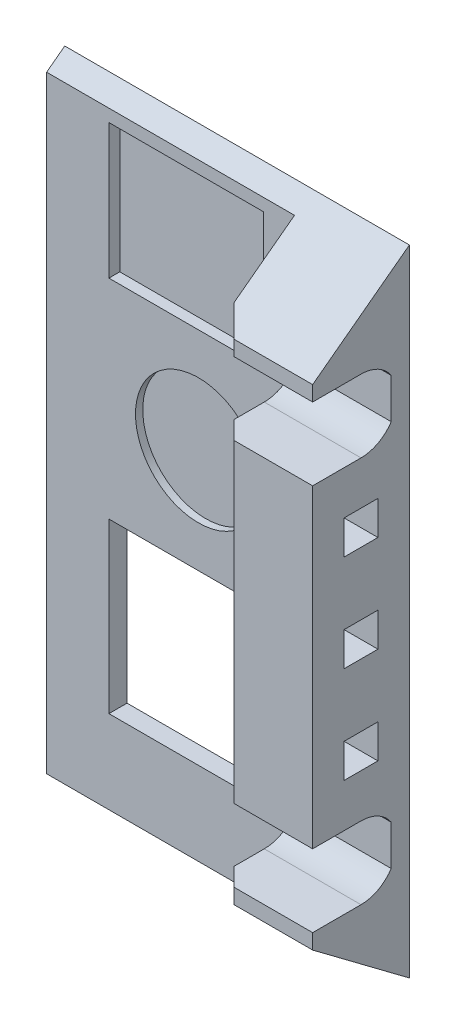
SolidWorks part; units mm, degrees
ref_plane "Plano frontal" through (0, 0, 0) normal (0, 0, 1) x (1, 0, 0)
ref_plane "Plano superior" through (0, 0, 0) normal (0, 1, 0) x (1, 0, 0)
ref_plane "Plano direito" through (0, 0, 0) normal (1, 0, 0) x (0, 0, -1)
sketch "Esboço1" plane through (0, 0, 0) normal (0, 0, 1) x (1, 0, 0)
  line L0 (-5, 0) -> (5, 0) construction
  line L1 (25, 0) -> (-25, 0) construction
  line L2 (0, 0) -> (0, -12.5) construction
  line L3 (25, -12.5) -> (-25, -12.5) construction
  line L4 (-21, 0) -> (-5, 0) construction
  line L5 (-25, -12.5) -> (-25, 12.5)
  line L6 (-25, 12.5) -> (25, 12.5)
  line L7 (0, 12.5) -> (0, 0) construction
  line L8 (20, -12.5) -> (-20, -12.5) construction
  line L12 (-15, -12.5) -> (15, -12.5)
  line L23 (21, 0) -> (5, 0) construction
  line L31 (25, -12.5) -> (25, 12.5)
  line L32 (-25, -12.5) -> (-15, -12.5)
  line L33 (15, -12.5) -> (25, -12.5)
  circle A0 centre (-13, 0) radius 8.3
  circle A1 centre (13, 0) radius 8.3
extrude "Ressalto-extrusão1" add sketch "Esboço1" along normal blind 1.5
sketch "Esboço2" plane through (0, 0, 1.5) normal (0, 0, 1) x (1, 0, 0)
  line L0 (-20, -12.5) -> (-25, -12.5)
  line L1 (0, -12.5) -> (0, 12.5) construction
  line L2 (20, -12.5) -> (-20, -12.5) construction
  line L3 (-25, -12.5) -> (25, -12.5) construction
  line L4 (22, -2.5) -> (22, -9.5)
  line L5 (-25, 12.5) -> (-25, -12.5) construction
  line L6 (-22, -9.5) -> (-15, -9.5)
  line L7 (-15, -9.5) -> (-15, -12.5)
  line L8 (-15, -12.5) -> (-20, -12.5)
  line L9 (-25, -12.5) -> (-25, -2.5)
  line L10 (-25, -2.5) -> (-22, -2.5)
  line L11 (-22, -2.5) -> (-22, -9.5)
  line L12 (25, -2.5) -> (22, -2.5)
  line L13 (25, -12.5) -> (25, -2.5)
  line L14 (15, -12.5) -> (20, -12.5)
  line L15 (25, 12.5) -> (-25, 12.5) construction
  line L16 (15, -9.5) -> (15, -12.5)
  line L17 (-25, 0) -> (25, 0) construction
  line L18 (25, -12.5) -> (25, 12.5) construction
  line L19 (22, -9.5) -> (15, -9.5)
  line L20 (20, -12.5) -> (25, -12.5)
  line L21 (20, 12.5) -> (-20, 12.5) construction
  line L22 (20, 12.5) -> (25, 12.5)
  line L23 (22, 9.5) -> (15, 9.5)
  line L24 (15, 9.5) -> (15, 12.5)
  line L25 (15, 12.5) -> (20, 12.5)
  line L26 (25, 12.5) -> (25, 2.5)
  line L27 (25, 2.5) -> (22, 2.5)
  line L28 (-22, 2.5) -> (-22, 9.5)
  line L29 (-25, 2.5) -> (-22, 2.5)
  line L30 (-25, 12.5) -> (-25, 2.5)
  line L31 (-15, 12.5) -> (-20, 12.5)
  line L32 (-15, 9.5) -> (-15, 12.5)
  line L33 (-22, 9.5) -> (-15, 9.5)
  line L34 (22, 2.5) -> (22, 9.5)
  line L35 (-20, 12.5) -> (-25, 12.5)
extrude "Ressalto-extrusão2" add sketch "Esboço2" along normal blind 6
sketch "Esboço3" plane through (0, -12.5, 0) normal (0, -1, 0) x (1, 0, 0)
  line L0 (-25, 3.75) -> (-15, 3.75) construction
  line L1 (-25, 7.5) -> (-25, 0) construction
  line L2 (-15, 7.5) -> (-15, 1.5) construction
  line L3 (-15, 3.75) -> (-20, 3.75) construction
  line L4 (-20, 3.75) -> (-20, 7.5) construction
  line L5 (-25, 7.5) -> (-15, 7.5) construction
  line L6 (0, 0) -> (0, 8.9122) construction
  line L7 (-21.4, 2.35) -> (-18.6, 2.35)
  line L8 (-21.4, 2.35) -> (-21.4, 5.15)
  line L9 (-21.4, 5.15) -> (-18.6, 5.15)
  line L10 (-18.6, 2.35) -> (-18.6, 5.15)
  line L11 (-21.4, 2.35) -> (-18.6, 5.15) construction
  line L12 (-21.4, 5.15) -> (-18.6, 2.35) construction
  line L13 (-25, 0) -> (25, 0) construction
  line L14 (21.4, 5.15) -> (18.6, 2.35) construction
  line L15 (21.4, 2.35) -> (18.6, 5.15) construction
  line L16 (18.6, 2.35) -> (18.6, 5.15)
  line L17 (21.4, 5.15) -> (18.6, 5.15)
  line L18 (21.4, 2.35) -> (21.4, 5.15)
  line L19 (21.4, 2.35) -> (18.6, 2.35)
extrude "Corte-extrusão1" cut sketch "Esboço3" against normal through all
sketch "Esboço4" plane through (-25, 0, 0) normal (-1, 0, 0) x (0, 0, 1)
  line L2 (3.75, 2.5) -> (3.75, 12.5) construction
  line L5 (3.75, -2.5) -> (3.75, -12.5) construction
  line L9 (0, 12.5) -> (7.5, 12.5) construction
  line L10 (5.15, 8.9) -> (2.35, 8.9)
  line L11 (5.15, 8.9) -> (5.15, 6.1)
  line L12 (5.15, 6.1) -> (2.35, 6.1)
  line L13 (2.35, 8.9) -> (2.35, 6.1)
  line L14 (5.15, 8.9) -> (2.35, 6.1) construction
  line L15 (5.15, 6.1) -> (2.35, 8.9) construction
  line L16 (5.15, -6.1) -> (2.35, -6.1)
  line L17 (5.15, -6.1) -> (5.15, -8.9)
  line L18 (5.15, -8.9) -> (2.35, -8.9)
  line L19 (2.35, -6.1) -> (2.35, -8.9)
  line L20 (5.15, -6.1) -> (2.35, -8.9) construction
  line L21 (5.15, -8.9) -> (2.35, -6.1) construction
  point P12 (3.75, 7.5)
  point P17 (3.75, -7.5)
  point P26 (3.75, 12.5)
extrude "Corte-extrusão2" cut sketch "Esboço4" against normal through all
sketch "Esboço6" plane through (0, 0, 0) normal (0, 0, -1) x (-1, 0, 0)
  line L0 (-25, 12.5) -> (-25, -12.5)
  line L1 (-30, -12.5) -> (-25, -12.5)
  line L2 (-30, -12.5) -> (-30, 12.5)
  line L3 (-30, 12.5) -> (-25, 12.5)
  line L4 (30, -12.5) -> (30, 12.5)
  line L5 (-30, -12.5) -> (30, 12.5) construction
  line L6 (-30, 12.5) -> (30, -12.5) construction
  line L7 (25, 12.5) -> (25, -12.5)
  line L8 (25, 12.5) -> (30, 12.5)
  line L9 (25, -12.5) -> (30, -12.5)
  point P0 (0, 0)
extrude "Ressalto-extrusão5" add sketch "Esboço6" against normal up to surface (7.5 mm away) up to face at (20.6667, -8.1667, 7.5)
sketch "Esboço7" plane through (30, 0, 0) normal (1, 0, 0) x (0, 0, -1)
  line L0 (-2.35, -6.1) -> (-5.15, -6.1) construction
  line L1 (-2.35, -8.9) -> (-2.35, -6.1) construction
  line L2 (-5.15, -8.9) -> (-2.35, -8.9) construction
  line L3 (-5.15, -6.1) -> (-5.15, -8.9) construction
  line L4 (-2.35, -6.1) -> (-5.15, -6.1)
  line L5 (-2.35, -8.9) -> (-2.35, -6.1)
  line L6 (-5.15, -8.9) -> (-2.35, -8.9)
  line L7 (-5.15, -6.1) -> (-5.15, -8.9)
  line L8 (-2.35, 6.1) -> (-2.35, 8.9) construction
  line L9 (-2.35, 8.9) -> (-5.15, 8.9) construction
  line L10 (-5.15, 8.9) -> (-5.15, 6.1) construction
  line L11 (-5.15, 6.1) -> (-2.35, 6.1) construction
  line L12 (-2.35, 6.1) -> (-2.35, 8.9)
  line L13 (-2.35, 8.9) -> (-5.15, 8.9)
  line L14 (-5.15, 8.9) -> (-5.15, 6.1)
  line L15 (-5.15, 6.1) -> (-2.35, 6.1)
extrude "Corte-extrusão3" cut sketch "Esboço7" against normal up to surface (60 mm away) up to face at (-30, 0, 3.75)
sketch "Esboço5" plane through (0, 0, 1.5) normal (0, 0, 1) x (1, 0, 0)
  line L0 (-9, -7.2726) -> (-9, -8.3958)
  line L1 (-17, -7.2726) -> (-17, -8.3958)
  line L2 (-17, 8.3958) -> (-17, 7.2726)
  line L3 (9, -7.2726) -> (9, -8.3958)
  line L4 (-9, 8.3958) -> (-9, 7.2726)
  line L8 (17, 8.3958) -> (17, 7.2726)
  line L10 (9, 8.3958) -> (9, 7.2726)
  line L13 (17, -7.2726) -> (17, -8.3958)
  circle A0 centre (-13, 0) radius 8.3 construction
  circle A1 centre (13, 0) radius 8.3 construction
  arc A2 (-17, 7.2726) -> (-17, -7.2726) centre (-13, 0) ccw
  arc A3 (17, -7.2726) -> (17, 7.2726) centre (13, 0) ccw
  arc A4 (-17, 8.3958) -> (-17, -8.3958) centre (-13, 0) ccw
  arc A5 (17, -8.3958) -> (17, 8.3958) centre (13, 0) ccw
  circle A6 centre (-13, 0) radius 8.3 construction
  circle A7 centre (-13, 0) radius 9.3 construction
  circle A8 centre (13, 0) radius 8.3 construction
  circle A9 centre (13, 0) radius 9.3 construction
  arc A12 (-9, -8.3958) -> (-9, 8.3958) centre (-13, 0) ccw
  arc A13 (-9, -7.2726) -> (-9, 7.2726) centre (-13, 0) ccw
  arc A14 (9, 7.2726) -> (9, -7.2726) centre (13, 0) ccw
  arc A15 (9, 8.3958) -> (9, -8.3958) centre (13, 0) ccw
  dimension "D1" = 1
  dimension "D2" = 1
extrude "Ressalto-extrusão3" add sketch "Esboço5" along normal blind 10
sketch "Esboço8" plane through (0, 0, 0) normal (0, 0, -1) x (-1, 0, 0)
  line L1 (30, 26.25) -> (-30, 26.25)
  line L2 (30, 26.25) -> (30, -26.25)
  line L3 (30, -26.25) -> (-30, -26.25)
  line L4 (-30, 26.25) -> (-30, -26.25)
  line L5 (30, 26.25) -> (-30, -26.25) construction
  line L6 (30, -26.25) -> (-30, 26.25) construction
  circle A0 centre (13, 0) radius 8.3
  circle A1 centre (-13, 0) radius 8.3
  point P6 (0, 0)
extrude "Ressalto-extrusão6" add sketch "Esboço8" against normal blind 1.5
sketch "Esboço9" plane through (0, 0, 1.5) normal (0, 0, 1) x (1, 0, 0)
  line L12 (-15, -12.5) -> (-15, -9.5)
  line L13 (-15, -9.5) -> (-22, -9.5)
  line L14 (-22, -9.5) -> (-22, -2.5)
  line L15 (-22, -2.5) -> (-25, -2.5)
  line L16 (-25, -2.5) -> (-25, 2.5)
  line L17 (-25, 2.5) -> (-22, 2.5)
  line L18 (-22, 2.5) -> (-22, 9.5)
  line L19 (-22, 9.5) -> (-15, 9.5)
  line L20 (-15, 9.5) -> (-15, 12.5)
  line L21 (-15, 12.5) -> (-30, 12.5)
  line L22 (-30, 12.5) -> (-30, -12.5)
  line L23 (-30, -12.5) -> (-15, -12.5)
  line L24 (-15, -12.5) -> (-15, -9.5)
  line L25 (-15, -9.5) -> (-22, -9.5)
  line L26 (-22, -9.5) -> (-22, -2.5)
  line L27 (-22, -2.5) -> (-25, -2.5)
  line L28 (-25, -2.5) -> (-25, 2.5)
  line L29 (-25, 2.5) -> (-22, 2.5)
  line L30 (-22, 2.5) -> (-22, 9.5)
  line L31 (-22, 9.5) -> (-15, 9.5)
  line L32 (-15, 9.5) -> (-15, 12.5)
  line L33 (-15, 12.5) -> (-30, 12.5)
  line L34 (-30, 12.5) -> (-30, -12.5)
  line L35 (-30, -12.5) -> (-15, -12.5)
  dimension "D1" = 0
extrude "Corte-extrusão4" cut sketch "Esboço9" along normal through all
sketch "Esboço10" plane through (0, 0, 1.5) normal (0, 0, 1) x (1, 0, 0)
  line L0 (-24.3, -26.25) -> (-24.3, 26.25)
  line L2 (-24.3, 26.25) -> (-22.3, 26.25)
  line L4 (-22.3, 12) -> (-17.3, 12)
  line L5 (-17.3, 12) -> (-17.3, -12)
  line L6 (-17.3, 0) -> (-24.3, 0) construction
  line L7 (-22.3, 20) -> (-22.3, 12)
  line L8 (-22.3, -20) -> (-22.3, -12)
  line L9 (-22.3, -12) -> (-17.3, -12)
  line L10 (-24.3, -26.25) -> (-22.3, -26.25)
  line L11 (-22.3, 12) -> (-22.3, 16) construction
  line L12 (-22.3, 16) -> (-22.3, 20) construction
  line L13 (-22.3, 20) -> (-17.3, 20)
  line L14 (-17.3, 20) -> (-17.3, 26.25)
  line L15 (-17.3, 26.25) -> (-22.3, 26.25)
  line L16 (-17.3, -26.25) -> (-22.3, -26.25)
  line L17 (-17.3, -20) -> (-17.3, -26.25)
  line L18 (-22.3, -20) -> (-17.3, -20)
  line L19 (-24.3, 0) -> (-22.3, 0) construction
  arc A0 (-17, 8.3958) -> (-17, -8.3958) centre (-13, 0) ccw construction
  point P22 (-22.3, 0)
  dimension "D1" = 12
extrude "Ressalto-extrusão7" add sketch "Esboço10" along normal blind 6.5
sketch "Esboço11" plane through (0, -26.25, 0) normal (0, -1, 0) x (1, 0, 0)
  line L0 (-22.3, 8) -> (-17.3, 8)
  line L1 (-17.3, 8) -> (-17.3, 1.5)
  line L2 (-22.3, 8) -> (-17.3, 1.5)
sketch "Esboço12" plane through (-24.3, 0, 0) normal (-1, 0, 0) x (0, 0, 1)
  line L0 (4, 0) -> (4, 16) construction
  line L1 (0, -26.25) -> (0, 26.25) construction
  line L3 (0, 0) -> (8, 0) construction
  circle A0 centre (4, 16) radius 1.65
  circle A1 centre (4, -16) radius 1.65
  dimension "D1" = 4
sketch "Esboço14" plane through (0, 0, 1.5) normal (0, 0, 1) x (1, 0, 0)
  line L4 (-30, -26.25) -> (-24.3, -26.25)
  line L5 (-24.3, -26.25) -> (-24.3, 26.25)
  line L6 (-24.3, 26.25) -> (-30, 26.25)
  line L7 (-30, 26.25) -> (-30, -26.25)
  line L8 (-30, -26.25) -> (-24.3, -26.25)
  line L9 (-24.3, -26.25) -> (-24.3, 26.25)
  line L10 (-24.3, 26.25) -> (-30, 26.25)
  line L11 (-30, 26.25) -> (-30, -26.25)
  dimension "D1" = 0
extrude "Corte-extrusão8" cut sketch "Esboço14" against normal blind 4.5
sketch "Esboço15" plane through (0, 0, 8) normal (0, 0, 1) x (1, 0, 0)
  line L1 (-17.3, -7.0993) -> (-17.3, 7.0993)
  line L2 (-17.3, -7.0993) -> (-17.3, 7.0993)
  arc A1 (-17.3, 7.0993) -> (-17.3, -7.0993) centre (-13, 0) ccw
  arc A2 (-17.3, 7.0993) -> (-17.3, -7.0993) centre (-13, 0) ccw
  dimension "D1" = 0
extrude "Corte-extrusão9" cut sketch "Esboço15" against normal through all
extrude "Corte-extrusão13" cut sketch "Esboço11" against normal up to surface (6.25 mm away) up to face at (-19.8, -20, 4.75)
sketch "Esboço17" plane through (0, 26.25, 0) normal (0, 1, 0) x (1, 0, 0)
  line L0 (-17.3, -1.5) -> (-17.3, -8)
  line L1 (-17.3, -8) -> (-22.3, -8)
  line L2 (-17.3, -8) -> (-24.3, -8) construction
  line L3 (-22.3, -8) -> (-17.3, -1.5)
extrude "Corte-extrusão14" cut sketch "Esboço17" against normal up to surface (6.25 mm away) up to face at (-19.8, 20, 4.75)
extrude "Corte-extrusão15" cut sketch "Esboço12" against normal blind 4.5
sketch "Esboço19" plane through (-24.3, 0, 0) normal (-1, 0, 0) x (0, 0, 1)
  line L0 (0, 26.25) -> (8, 26.25)
  line L1 (8, 26.25) -> (8, 20.25)
  line L2 (8, 26.25) -> (8, -26.25) construction
  line L3 (8, 20.25) -> (0, 26.25)
  line L4 (0, 0) -> (8, 0) construction
  line L5 (8, -20.25) -> (0, -26.25)
  line L6 (8, -26.25) -> (8, -20.25)
  line L7 (0, -26.25) -> (8, -26.25)
extrude "Corte-extrusão17" cut sketch "Esboço19" against normal through all
sketch "Esboço20" plane through (-22.3, 0, 0) normal (1, 0, 0) x (0, 0, -1)
  circle A0 centre (-4, -16) radius 3.5
  circle A1 centre (-4, 16) radius 3.5
extrude "Corte-extrusão18" cut sketch "Esboço20" along normal blind 5
sketch "Esboço21" plane through (-24.3, 0, 0) normal (-1, 0, 0) x (0, 0, 1)
  line L4 (0, 26.25) -> (0, -26.25)
  line L5 (0, -26.25) -> (8, -20.25)
  line L6 (8, -20.25) -> (8, 20.25)
  line L7 (8, 20.25) -> (0, 26.25)
  line L8 (0, 26.25) -> (0, -26.25)
  line L9 (0, -26.25) -> (8, -20.25)
  line L10 (8, -20.25) -> (8, 20.25)
  line L11 (8, 20.25) -> (0, 26.25)
  circle A0 centre (4, -16) radius 1.65 construction
  circle A1 centre (4, -16) radius 1.65
  circle A2 centre (4, 16) radius 1.65 construction
  circle A3 centre (4, 16) radius 1.65
  dimension "D1" = 0
extrude "Ressalto-extrusão8" add sketch "Esboço21" along normal blind 2.95
sketch "Esboço22" plane through (30, 0, 0) normal (1, 0, 0) x (0, 0, -1)
  line L0 (-2.35, -6.1) -> (-5.15, -6.1) construction
  line L1 (-2.35, -8.9) -> (-2.35, -6.1) construction
  line L2 (-5.15, -8.9) -> (-2.35, -8.9) construction
  line L3 (-5.15, -6.1) -> (-5.15, -8.9) construction
  line L4 (-2.35, 8.9) -> (-5.15, 8.9) construction
  line L5 (-5.15, 8.9) -> (-5.15, 6.1) construction
  line L6 (-2.35, 6.1) -> (-2.35, 8.9) construction
  line L7 (-5.15, 6.1) -> (-2.35, 6.1) construction
  line L8 (-1.5, -25.125) -> (0, -26.25)
  line L9 (0, -26.25) -> (0, 26.25)
  line L10 (0, 26.25) -> (-1.5, 25.125)
  line L11 (-1.5, 25.125) -> (-1.5, 12.5)
  line L12 (-1.5, 12.5) -> (-7.5, 12.5)
  line L13 (-7.5, 12.5) -> (-7.5, -12.5)
  line L14 (-7.5, -12.5) -> (-1.5, -12.5)
  line L15 (-1.5, -12.5) -> (-1.5, -25.125)
  line L16 (-1.5, -25.125) -> (0, -26.25)
  line L17 (0, -26.25) -> (0, 26.25)
  line L18 (0, 26.25) -> (-1.5, 25.125)
  line L19 (-1.5, 25.125) -> (-1.5, 12.5)
  line L20 (-1.5, 12.5) -> (-7.5, 12.5)
  line L21 (-7.5, 12.5) -> (-7.5, -12.5)
  line L22 (-7.5, -12.5) -> (-1.5, -12.5)
  line L23 (-1.5, -12.5) -> (-1.5, -25.125)
  line L24 (-2.35, -6.1) -> (-5.15, -6.1)
  line L25 (-2.35, -8.9) -> (-2.35, -6.1)
  line L26 (-5.15, -8.9) -> (-2.35, -8.9)
  line L27 (-5.15, -6.1) -> (-5.15, -8.9)
  line L28 (-2.35, 8.9) -> (-5.15, 8.9)
  line L29 (-5.15, 8.9) -> (-5.15, 6.1)
  line L30 (-2.35, 6.1) -> (-2.35, 8.9)
  line L31 (-5.15, 6.1) -> (-2.35, 6.1)
  dimension "D1" = 0
extrude "Ressalto-extrusão9" add sketch "Esboço22" along normal blind 1.25
sketch "Esboço23" plane through (0, 0, 7.5) normal (0, 0, 1) x (1, 0, 0)
  line L12 (25, -2.5) -> (22, -2.5)
  line L13 (22, -2.5) -> (22, -9.5)
  line L14 (22, -9.5) -> (15, -9.5)
  line L15 (15, -9.5) -> (15, -12.5)
  line L16 (15, -12.5) -> (31.25, -12.5)
  line L17 (31.25, -12.5) -> (31.25, 12.5)
  line L18 (31.25, 12.5) -> (15, 12.5)
  line L19 (15, 12.5) -> (15, 9.5)
  line L20 (15, 9.5) -> (22, 9.5)
  line L21 (22, 9.5) -> (22, 2.5)
  line L22 (22, 2.5) -> (25, 2.5)
  line L23 (25, 2.5) -> (25, -2.5)
  line L24 (25, -2.5) -> (22, -2.5)
  line L25 (22, -2.5) -> (22, -9.5)
  line L26 (22, -9.5) -> (15, -9.5)
  line L27 (15, -9.5) -> (15, -12.5)
  line L28 (15, -12.5) -> (31.25, -12.5)
  line L29 (31.25, -12.5) -> (31.25, 12.5)
  line L30 (31.25, 12.5) -> (15, 12.5)
  line L31 (15, 12.5) -> (15, 9.5)
  line L32 (15, 9.5) -> (22, 9.5)
  line L33 (22, 9.5) -> (22, 2.5)
  line L34 (22, 2.5) -> (25, 2.5)
  line L35 (25, 2.5) -> (25, -2.5)
  dimension "D1" = 0
extrude "Corte-extrusão19" cut sketch "Esboço23" against normal up to surface (6 mm away) up to face at (13, 0, 1.5)
sketch "Esboço24" plane through (0, 0, 1.5) normal (0, 0, 1) x (1, 0, 0)
  line L0 (31.25, -25.125) -> (-17.3, -25.125) construction
  line L1 (31.25, 25.125) -> (23.25, 25.125)
  line L2 (31.25, 25.125) -> (31.25, -25.125)
  line L3 (31.25, -25.125) -> (23.25, -25.125)
  line L4 (23.25, 25.125) -> (23.25, -25.125)
extrude "Ressalto-extrusão10" add sketch "Esboço24" along normal up to surface (6.5 mm away) up to face at (-21.875, 0, 8)
sketch "Esboço25" plane through (0, 25.125, 0) normal (0, 1, 0) x (1, 0, 0)
  line L1 (23.25, -8) -> (23.25, -1.5) construction
  line L2 (23.25, -6.5) -> (23.25, -8)
  line L3 (23.25, -8) -> (24.75, -8)
  line L4 (23.25, -8) -> (31.25, -8) construction
  line L5 (24.75, -8) -> (23.25, -6.5)
extrude "Corte-extrusão20" cut sketch "Esboço25" against normal through all
sketch "Esboço26" plane through (31.25, 0, 0) normal (1, 0, 0) x (0, 0, -1)
  line L0 (-8, 0) -> (0, 0) construction
  line L1 (-8, 25.125) -> (-8, -25.125) construction
  line L2 (0, 0) -> (-4, 0) construction
  line L3 (-4, 0) -> (-4, -8) construction
  line L4 (-2.6, 1.4) -> (-5.4, 1.4)
  line L5 (-2.6, -6.6) -> (-5.4, -6.6)
  line L6 (-2.6, -6.6) -> (-2.6, -9.4)
  line L7 (-2.6, -9.4) -> (-5.4, -9.4)
  line L8 (-5.4, -6.6) -> (-5.4, -9.4)
  line L9 (-2.6, -6.6) -> (-5.4, -9.4) construction
  line L10 (-2.6, -9.4) -> (-5.4, -6.6) construction
  line L11 (-2.6, 1.4) -> (-2.6, -1.4)
  line L12 (-2.6, -1.4) -> (-5.4, -1.4)
  line L13 (-5.4, 1.4) -> (-5.4, -1.4)
  line L14 (-2.6, 1.4) -> (-5.4, -1.4) construction
  line L15 (-2.6, -1.4) -> (-5.4, 1.4) construction
  line L16 (-2.6, 9.4) -> (-5.4, 9.4)
  line L17 (-2.6, 9.4) -> (-2.6, 6.6)
  line L18 (-2.6, 6.6) -> (-5.4, 6.6)
  line L19 (-5.4, 9.4) -> (-5.4, 6.6)
  line L20 (-2.6, 9.4) -> (-5.4, 6.6) construction
  line L21 (-2.6, 6.6) -> (-5.4, 9.4) construction
  dimension "D1" = 3
extrude "Corte-extrusão21" cut sketch "Esboço26" against normal up to next
sketch "Esboço27" plane through (31.25, 0, 0) normal (1, 0, 0) x (0, 0, -1)
  line L0 (-4, 19) -> (-8, 19)
  line L1 (-8, -20.25) -> (-8, -25.125)
  line L2 (-8, 25.125) -> (-8, -25.125) construction
  line L3 (-8, 25.125) -> (-8, 20.25)
  line L4 (-8, 19) -> (-8, 13)
  line L5 (-8, 13) -> (-4, 13)
  line L6 (-4, -13) -> (-8, -13)
  line L7 (-8, -13) -> (-8, -19)
  line L8 (-8, -19) -> (-4, -19)
  line L9 (-1.5, 25.125) -> (-1.5, -25.125) construction
  line L10 (-1.5, 17.6583) -> (-1.5, 14.3417)
  line L11 (-1.5, -14.3417) -> (-1.5, -17.6583)
  line L13 (-1.5, 25.125) -> (-8, 20.25) construction
  line L17 (-8, -20.25) -> (-1.5, -25.125) construction
  line L21 (-1.5, 25.125) -> (-8, 20.25)
  line L25 (-8, -20.25) -> (-1.5, -25.125)
  line L28 (-1.5, 25.125) -> (-8, 25.125)
  line L30 (-1.5, -25.125) -> (-8, -25.125)
  circle A0 centre (-4, -16) radius 1.65 construction
  circle A1 centre (-4, 16) radius 1.65 construction
  circle A2 centre (-4, -16) radius 1.65 construction
  circle A3 centre (-4, 16) radius 1.65 construction
  arc A4 (-4, -19) -> (-1.5, -17.6583) centre (-4, -16) ccw
  arc A5 (-4, 13) -> (-1.5, 14.3417) centre (-4, 16) ccw
  arc A6 (-1.5, 17.6583) -> (-4, 19) centre (-4, 16) ccw
  arc A7 (-1.5, -14.3417) -> (-4, -13) centre (-4, -16) ccw
extrude "Corte-extrusão22" cut sketch "Esboço27" against normal up to next
sketch "Esboço28" plane through (0, 0, 8) normal (0, 0, 1) x (1, 0, 0)
  line L0 (-27.25, -12) -> (-27.25, 12)
  line L1 (-27.25, -20.25) -> (-27.25, 20.25) construction
  line L2 (-27.25, 12) -> (-24.8, 12)
  line L3 (-22.3, 9.5) -> (-22.3, -9.5)
  line L4 (-24.8, -12) -> (-27.25, -12)
  line L5 (-27.25, -12) -> (-27.25, 12)
  arc A0 (-24.8, 12) -> (-22.3, 9.5) centre (-24.8, 9.5) cw
  arc A1 (-22.3, -9.5) -> (-24.8, -12) centre (-24.8, -9.5) cw
  point P9 (-22.3, 12)
  line M2 (-27.25, 20.25) -> (-27.25, -20.25)
  dimension "D1" = 2.5
extrude "Corte-extrusão23" cut sketch "Esboço28" against normal up to surface (6.5 mm away) contours A1 L3 A0 L2 L4 M2 up to face at (13, 0, 1.5)
sketch "Esboço29" plane through (0, 0, 8) normal (0, 0, 1) x (1, 0, 0)
  line L0 (-19.8, -12) -> (-19.8, -12.4492)
  line L6 (-19.8, 12) -> (-19.8, 12.9071)
  line L7 (-19.8, 12.9071) -> (-15.7505, 12.9071)
  line L8 (-15.7505, 12.9071) -> (-15.7505, 9.5)
  line L9 (-15.7505, 9.5) -> (-17.3, 9.5)
  line L10 (-17.3, -9.5) -> (-15.2259, -9.5)
  line L11 (-15.2259, -9.5) -> (-15.2259, -14.1397)
  line L12 (-15.2259, -14.1397) -> (-19.8, -14.1397)
  line L13 (-19.8, -14.1397) -> (-19.8, -12.4492)
  arc A0 (-19.8, -12) -> (-17.3, -9.5) centre (-19.8, -9.5) ccw
  arc A1 (-19.8, 12) -> (-17.3, 9.5) centre (-19.8, 9.5) cw
  point P16 (-17.3, -12)
  point P19 (-17.3, 12)
  dimension "D1" = 2.5
extrude "Corte-extrusão24" cut sketch "Esboço29" against normal up to surface (6.5 mm away) up to face at (13, 0, 1.5)
sketch "Esboço30" plane through (0, 0, 8) normal (0, 0, 1) x (1, 0, 0)
  line L0 (-27.25, 12) -> (-17, 12)
  line L1 (-17, 12) -> (-17, 8.3958)
  line L2 (-27.25, -12) -> (-17, -12)
  line L3 (-17, -12) -> (-17, -8.3958)
  line L4 (-27.25, -12) -> (-27.25, 12)
  arc A0 (-17, 8.3958) -> (-17, -8.3958) centre (-13, 0) ccw construction
  arc A1 (-17, 8.3958) -> (-17, -8.3958) centre (-13, 0) ccw
extrude "Corte-extrusão25" cut sketch "Esboço30" against normal up to surface (6.5 mm away) up to face at (-6.4691, 0, 1.5)
sketch "Esboço31" plane through (-27.25, 0, 0) normal (-1, 0, 0) x (0, 0, 1)
  line L8 (5.5, -12) -> (8, -12)
  line L9 (8, -12) -> (8, -14.5)
  line L10 (5.5, 12) -> (8, 12)
  line L11 (8, 12) -> (8, 14.5)
  arc A0 (5.5, -12) -> (8, -14.5) centre (5.5, -14.5) cw
  arc A1 (5.5, 12) -> (8, 14.5) centre (5.5, 14.5) ccw
  point P18 (8, -12)
  point P21 (8, 12)
  dimension "D1" = 2.5
extrude "Corte-extrusão26" cut sketch "Esboço31" against normal up to surface (4.95 mm away) up to face at (-22.3, 16, 5.65)
sketch "Esboço33" plane through (0, 0, 1.5) normal (0, 0, 1) x (1, 0, 0)
  circle A0 centre (13, 0) radius 9.3
  circle A1 centre (-13, 0) radius 9.3
extrude "Corte-extrusão27" cut sketch "Esboço33" along normal through all
sketch "Esboço34" plane through (0, 0, 0) normal (0, 0, -1) x (-1, 0, 0)
  circle A0 centre (-13, 0) radius 8.3 construction
  circle A1 centre (13, 0) radius 8.3 construction
  circle A2 centre (-13, 0) radius 8.3
  circle A3 centre (13, 0) radius 8.3
extrude "Ressalto-extrusão11" add sketch "Esboço34" against normal up to surface (1.5 mm away) up to face at (-4.7, 0, 1.5)
sketch "Esboço49" plane through (-27.25, 0, 0) normal (-1, 0, 0) x (0, 0, 1)
  line L0 (0, 26.25) -> (0, -26.25) construction
  circle A0 centre (0, 0) radius 41.4032
extrude "Corte-extrusão37" cut sketch "Esboço49" against normal blind 28.5
sketch "Esboço50" plane through (0, 0, 0) normal (0, 0, -1) x (-1, 0, 0)
  line L0 (-8.901, -17.2403) -> (-8.901, -5.3023) construction
  line L1 (-19.696, -17.2403) -> (-8.901, -17.2403) construction
  line L2 (-19.696, -17.2403) -> (-19.696, -5.3023) construction
  line L3 (-19.696, -5.3023) -> (-8.901, -5.3023) construction
  line L4 (-19.6325, 23.0949) -> (-8.901, 23.0949) construction
  line L5 (-8.901, 13.9509) -> (-8.901, 23.0949) construction
  line L6 (-19.6325, 13.9509) -> (-8.901, 13.9509) construction
  line L7 (-19.696, 14.0144) -> (-19.696, 23.0314) construction
  line L8 (-31.25, -26.0398) -> (-1.25, -26.0398) construction
  line L9 (-31.25, -26.1449) -> (-31.25, 26.4602) construction
  line L10 (-7.901, -18.2403) -> (-7.901, -4.3023)
  line L11 (-20.696, -4.3023) -> (-7.901, -4.3023)
  line L12 (-20.696, -18.2403) -> (-20.696, -4.3023)
  line L13 (-20.696, -18.2403) -> (-7.901, -18.2403)
  line L16 (-7.901, 12.9509) -> (-20.696, 12.9509)
  line L17 (-7.901, 12.9509) -> (-7.901, 24.0949)
  line L18 (-7.901, 24.0949) -> (-20.696, 24.0949)
  line L20 (-20.696, 12.9509) -> (-20.696, 24.0949)
  dimension "D1" = 1
extrude "Corte-extrusão38" cut sketch "Esboço50" against normal through all
sketch "Esboço51" plane through (0, 0, 1.5) normal (0, 0, 1) x (1, 0, 0)
  line L0 (14.2985, 12.9509) -> (14.2985, -4.3023) construction
  line L1 (7.901, 12.9509) -> (20.696, 12.9509) construction
  line L2 (20.696, -4.3023) -> (7.901, -4.3023) construction
  circle A0 centre (15.2985, 4.3243) radius 5.2
  dimension "D1" = 1
extrude "Corte-extrusão39" cut sketch "Esboço51" against normal blind 0.6
sketch "Esboço52" plane through (1.25, 0, 0) normal (-1, 0, 0) x (0, 0, 1)
  line L0 (0, 26.25) -> (0, -26.25) construction
  circle A0 centre (0, 0) radius 31.4706
extrude "Corte-extrusão40" cut sketch "Esboço52" against normal blind 1.5
sketch "Esboço54" plane through (0, 0, 0) normal (0, 0, -1) x (-1, 0, 0)
  circle A0 centre (-15.2985, 4.3243) radius 3
  circle A1 centre (-15.2985, 4.3243) radius 5
extrude "Corte-extrusão41" cut sketch "Esboço54" against normal blind 0.3
sketch "Esboço56" plane through (0, 0, 0) normal (0, 0, -1) x (-1, 0, 0)
  line L0 (-7.901, 12.9509) -> (-7.901, 24.0949) construction
  line L1 (-20.696, 12.9509) -> (-7.901, 12.9509) construction
  line L2 (-20.696, 24.0949) -> (-20.696, 12.9509) construction
  line L3 (-7.901, 24.0949) -> (-20.696, 24.0949) construction
  line L4 (-7.901, 12.9509) -> (-7.901, 24.0949)
  line L5 (-20.696, 12.9509) -> (-7.901, 12.9509)
  line L6 (-20.696, 24.0949) -> (-20.696, 12.9509)
  line L7 (-7.901, 24.0949) -> (-20.696, 24.0949)
extrude "Ressalto-extrusão13" add sketch "Esboço56" against normal blind 0.6
sketch "Esboço57" plane through (0, 0, 0) normal (0, 0, 1) x (1, 0, 0)
  line L0 (8.201, 13.2509) -> (20.396, 13.2509)
  line L1 (20.396, 13.2509) -> (20.396, 23.7949)
  line L2 (20.396, 23.7949) -> (8.201, 23.7949)
  line L3 (8.201, 23.7949) -> (8.201, 13.2509)
  line L4 (7.901, 12.9509) -> (20.696, 12.9509)
  line L5 (20.696, 12.9509) -> (20.696, 24.0949)
  line L6 (20.696, 24.0949) -> (7.901, 24.0949)
  line L7 (7.901, 24.0949) -> (7.901, 12.9509)
  line L8 (7.901, 12.9509) -> (20.696, 12.9509)
  line L9 (20.696, 12.9509) -> (20.696, 24.0949)
  line L10 (20.696, 24.0949) -> (7.901, 24.0949)
  line L11 (7.901, 24.0949) -> (7.901, 12.9509)
  dimension "D1" = 0
  dimension "D2" = 0.3
extrude "Corte-extrusão44" cut sketch "Esboço57" along normal blind 0.3
